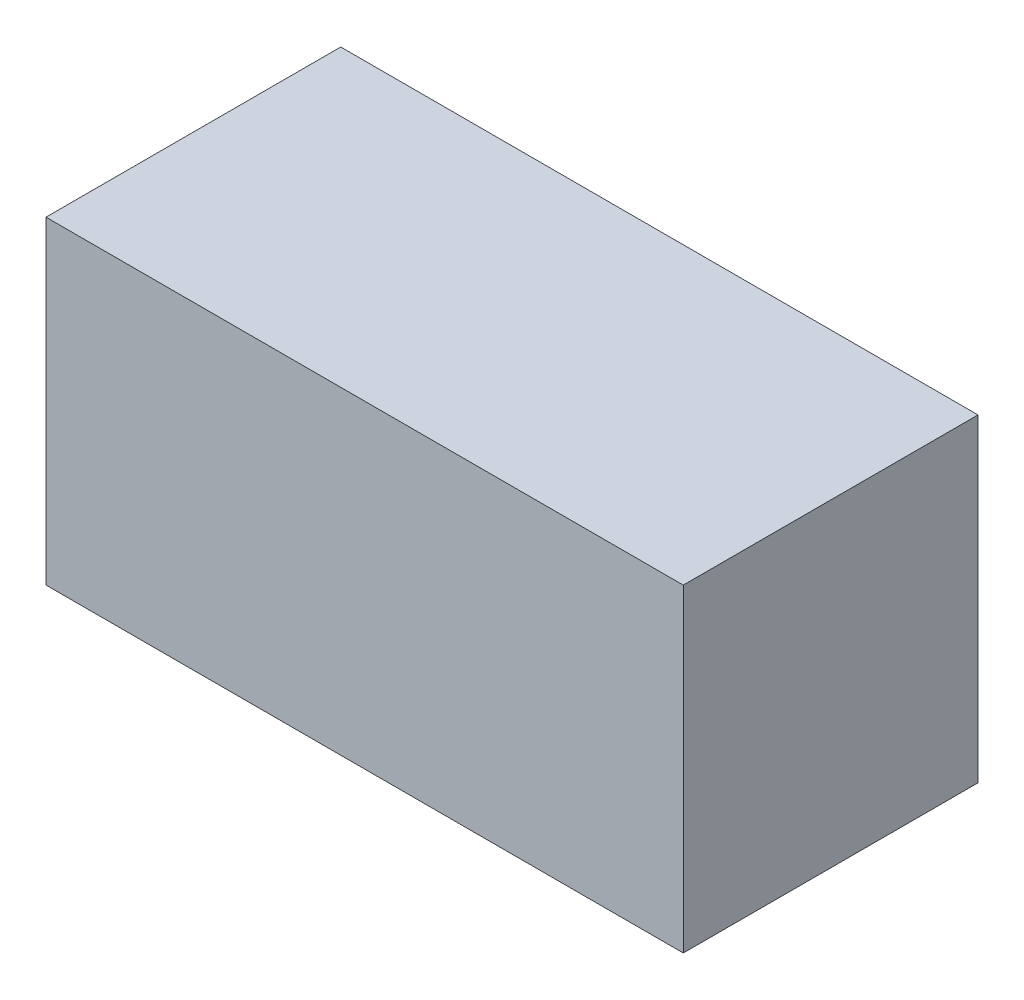
SolidWorks part; units mm, degrees
ref_plane "Спереди" through (0, 0, 0) normal (0, 0, 1) x (1, 0, 0)
ref_plane "Сверху" through (0, 0, 0) normal (0, 1, 0) x (1, 0, 0)
ref_plane "Справа" through (0, 0, 0) normal (1, 0, 0) x (0, 0, -1)
sketch "Эскиз1" plane through (0, 0, 0) normal (0, 0, 1) x (1, 0, 0)
  line L1 (-400, 200) -> (400, 200)
  line L2 (-400, 200) -> (-400, -200)
  line L3 (-400, -200) -> (400, -200)
  line L4 (400, 200) -> (400, -200)
  line L5 (-400, 200) -> (400, -200) construction
  line L6 (-400, -200) -> (400, 200) construction
  point P0 (0, 0)
extrude "Бобышка-Вытянуть1" add sketch "Эскиз1" along normal blind 370 contours L2 L1 L4 L3
